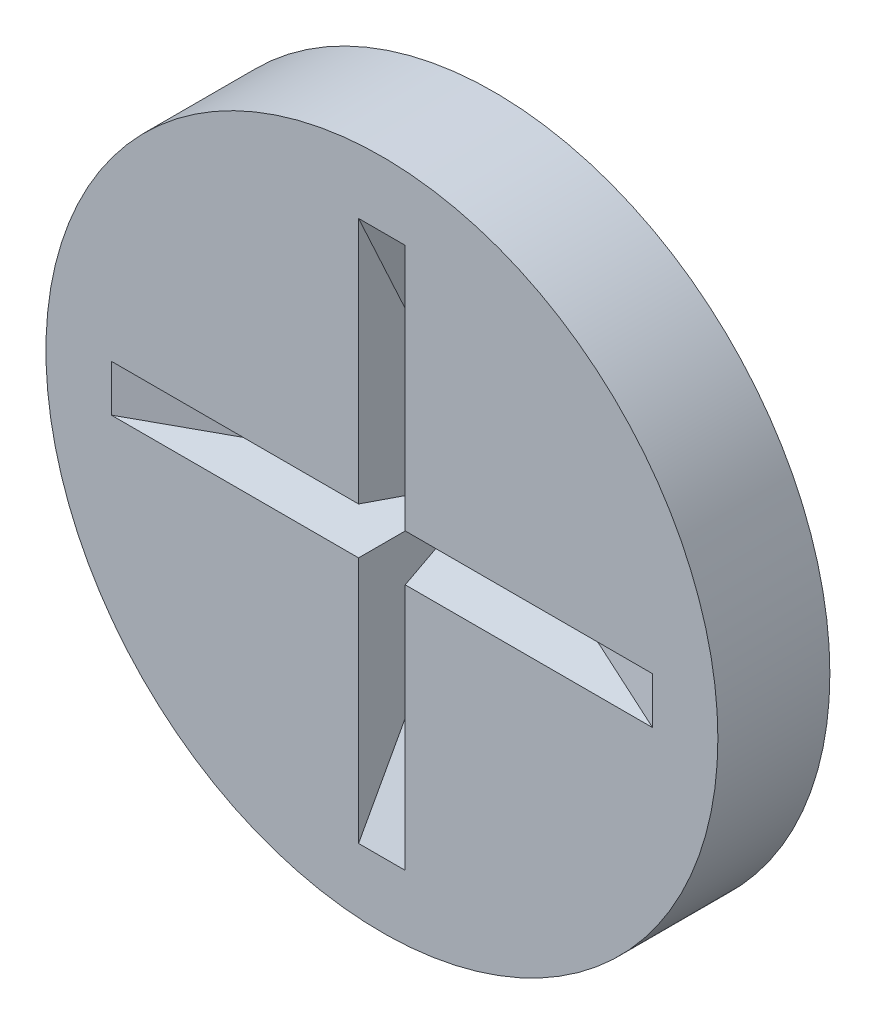
SolidWorks part; units mm, degrees
ref_plane "前基準面" through (0, 0, 0) normal (0, 0, 1) x (1, 0, 0)
ref_plane "上基準面" through (0, 0, 0) normal (0, 1, 0) x (1, 0, 0)
ref_plane "右基準面" through (0, 0, 0) normal (1, 0, 0) x (0, 0, -1)
sketch "草圖2" plane through (0, 0, 0) normal (0, 0, 1) x (1, 0, 0)
  circle A0 centre (0, 0) radius 3.6
  dimension "D1" = 7.2
extrude "伸長1" add sketch "草圖2" along normal blind 1.2
sketch "草圖3" plane through (0, 0, 0) normal (0, 0, -1) x (-1, 0, 0)
  circle A0 centre (0, 0) radius 1
  dimension "D1" = 2
extrude "伸長2" add sketch "草圖3" along normal blind 1.2
sketch "草圖4" plane through (0, 0, 1.2) normal (0, 0, 1) x (1, 0, 0)
  line L1 (-0.25, 2.9) -> (0.25, 2.9)
  line L2 (-0.25, 2.9) -> (-0.25, -2.9)
  line L3 (-0.25, -2.9) -> (0.25, -2.9)
  line L4 (0.25, 2.9) -> (0.25, -2.9)
  line L5 (-0.25, 2.9) -> (0.25, -2.9) construction
  line L6 (-0.25, -2.9) -> (0.25, 2.9) construction
  point P0 (0, 0)
  dimension "D1" = 5.8
  dimension "D2" = 0.5
sketch "草圖5" plane through (0, 0, 0) normal (1, 0, 0) x (0, 0, -1)
  point P0 (0, 0)
loft "除料-疊層拉伸1" cut profiles "草圖4", "草圖5"
pattern_circular "環狀複製排列2" count 4 over 360 about axis through (0, 0, 0) along (0, 0, 1) of "除料-疊層拉伸1"
